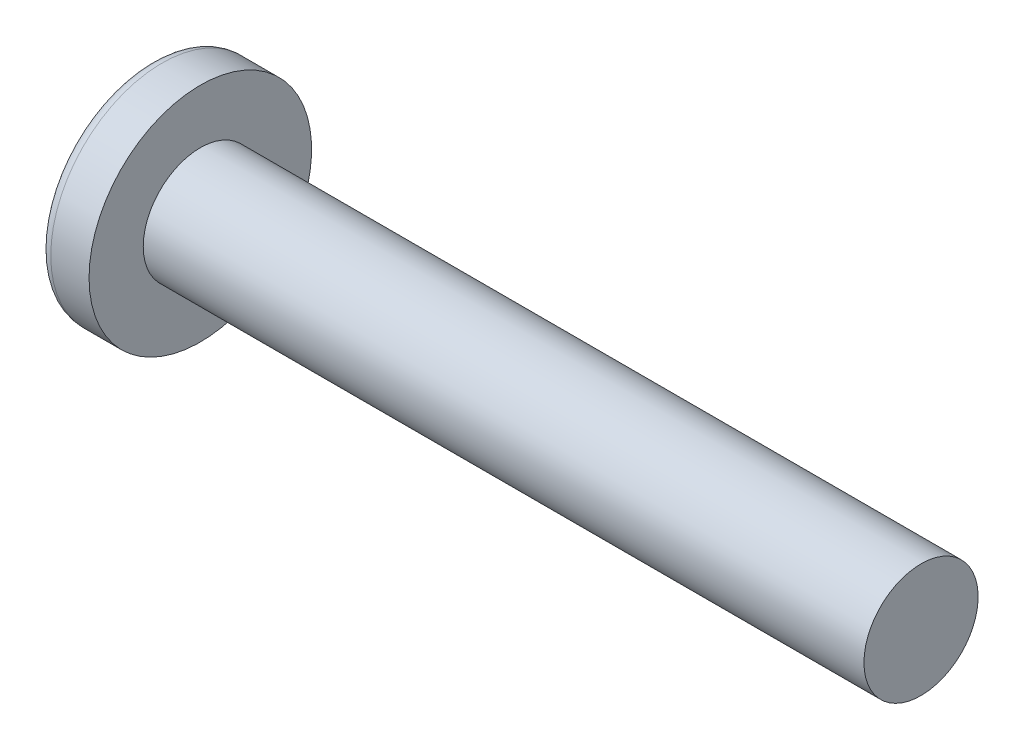
SolidWorks part; units mm, degrees
ref_plane "Plane1" through (0, 0, 0) normal (0, 0, 1) x (1, 0, 0)
ref_plane "Plane2" through (0, 0, 0) normal (0, 1, 0) x (1, 0, 0)
ref_plane "Plane3" through (0, 0, 0) normal (1, 0, 0) x (0, 0, -1)
sketch "BodySke" plane through (0, 0, 0) normal (0, 0, 1) x (1, 0, 0)
  line L0 (1.8034, 1.2573) -> (1.8034, 2.4511)
  line L1 (2.0307, 6.35) -> (2.0307, -3.175) construction
  line L2 (-25.4, 0) -> (127, 0) construction
  line L3 (17.6784, 0) -> (0, 0)
  line L4 (1.8034, 1.2573) -> (17.6784, 1.2573)
  line L5 (17.6784, 1.2573) -> (17.6784, 0)
  line L6 (0.9605, 2.4511) -> (1.8034, 2.4511)
  line L7 (1.8034, -1.2573) -> (17.6784, -1.2573) construction
  line L8 (1.8034, 6.35) -> (1.8034, -3.175) construction
  arc A0 (0.7542, 2.3452) -> (0, 0) centre (4.0234, 0) ccw
  arc A2 (0.7542, 2.3452) -> (0.9605, 2.4511) centre (0.9605, 2.1971) cw
revolve "Base-Revolve" add sketch "BodySke" angle 360 about L2
cosmetic thread "ThreadCosmetic" [suppressed] parameters "Thread_length"=15.4203, "Thread_minor"=1.9761
sketch "Sketch3" plane through (0, 0, 0) normal (1, 0, 0) x (0, 0, -1)
  line L0 (0.3683, -1.5875) -> (-0.3683, -1.5875)
  line L1 (0.3683, -1.5875) -> (0.3683, 1.5875)
  line L2 (-0.3683, 1.5875) -> (0.3683, 1.5875)
  line L3 (-0.3683, 1.5875) -> (-0.3683, -1.5875)
ref_plane "Plane4" through (1.7526, 0, 0) normal (1, 0, 0) x (0, 0, -1)
sketch "Sketch4" plane through (1.7526, 0, 0) normal (1, 0, 0) x (0, 0, -1)
  line L0 (0.1842, -0.1842) -> (-0.1841, -0.1842)
  line L1 (0.1842, -0.1842) -> (0.1842, 0.1842)
  line L2 (-0.1842, 0.1842) -> (0.1842, 0.1842)
  line L3 (-0.1842, 0.1842) -> (-0.1841, -0.1842)
loft "Cut-Loft1" cut profiles "Sketch3", "Sketch4"
pattern_circular "CirPattern1" count 2 every 90 about axis through (0, 0, 0) along (1, 0, 0) of "Cut-Loft1"
sketch "ThdSchSke" plane through (0, 0, 0) normal (0, 0, 1) x (1, 0, 0)
  line L0 (2.2581, -0.9881) -> (2.0695, -1.2573)
  line L1 (2.2581, -0.9881) -> (2.4466, -1.2573)
  line L2 (2.4466, -1.2573) -> (2.4466, -1.5716)
  line L3 (-3.175, 0) -> (5.1513, 0) construction
  line L5 (2.4466, -1.5716) -> (2.0695, -1.5716)
  line L6 (2.0695, -1.5716) -> (2.0695, -1.2573)
  dimension "SideAngle" = 55
  dimension "VeeAngle" = 70
revolve "ThreadSchematic" [suppressed] cut sketch "ThdSchSke" angle 360 about L3
pattern_linear "ThdSchPat" [suppressed]
equation "\"D1@Sketch3\" = \"Cross_dia@Sketch3\" / 2"
equation "\"D2@Sketch3\" = \"Cross_width@Sketch3\" / 2"
equation "\"D1@Sketch4\" = \"Cross_width@Sketch3\" *.5"
equation "\"D2@Sketch4\" = \"D1@Sketch4\""
equation "\"D3@Sketch4\" = \"D1@Sketch4\" / 2"
equation "\"D4@Sketch4\" = \"D2@Sketch4\" / 2"
equation "\"Thread_length@ThreadCosmetic\" = ((sgn( (\"Length@BodySke\" - \"Advance@BodySke\" ) - \"Thread_nom@BodySke\" )-1)*( (\"Length@BodySke\" - \"Advance@BodySke\" ) - \"Thread_nom@BodySke\" ))/-2+ \"Thread_nom@BodySke\""
equation "\"Thread_minor@ThdSchSke\" = \"Thread_minor@ThreadCosmetic\""
equation "\"Diameter@ThdSchSke\" = \"Diameter@BodySke\""
equation "\"Overcut@ThdSchSke\" = \"Diameter@BodySke\" * 1.25"
equation "\"Start@ThdSchSke\" = \"Head_ht@BodySke\" + \"Length@BodySke\" - \"Thread_length@ThreadCosmetic\"  '---Non-countersunk---"
equation "\"Num_threads@ThdSchPat\" = int( \"Thread_length@ThreadCosmetic\" / \"Advance@BodySke\" + 0.999 )  + 1"
equation "\"Advance@ThdSchPat\" = \"Thread_length@ThreadCosmetic\" /  (\"Num_threads@ThdSchPat\" - 1) 'relax it"
